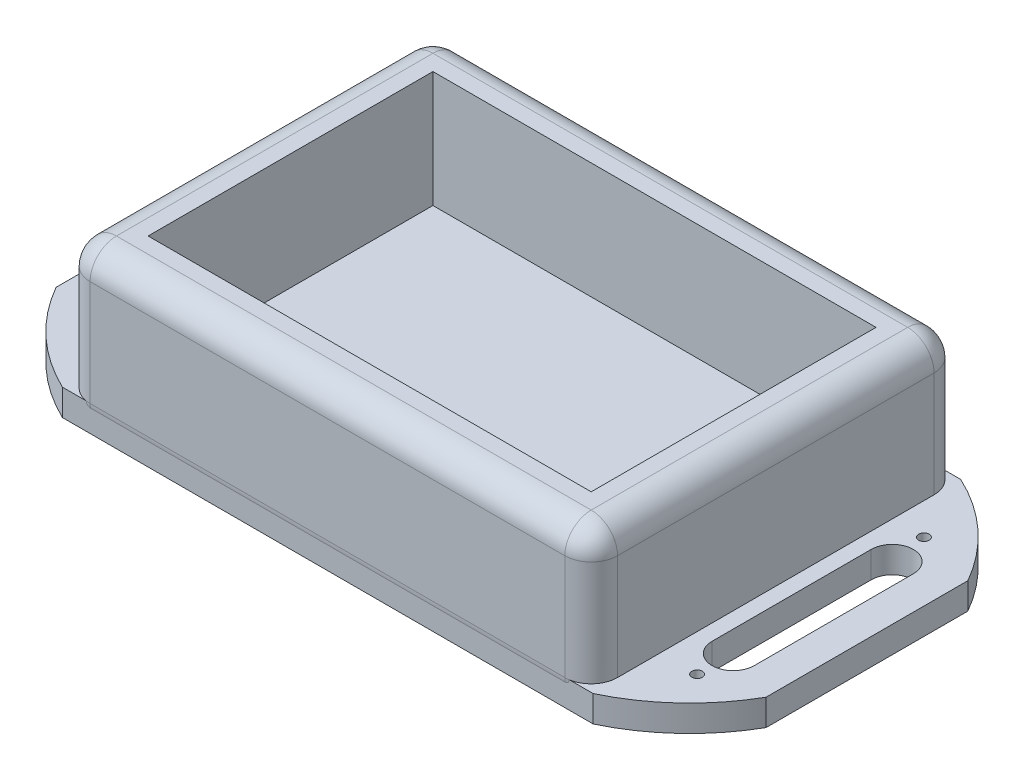
SolidWorks part; units mm, degrees
ref_plane "Front Plane" through (0, 0, 0) normal (0, 0, 1) x (1, 0, 0)
ref_plane "Top Plane" through (0, 0, 0) normal (0, 1, 0) x (1, 0, 0)
ref_plane "Right Plane" through (0, 0, 0) normal (1, 0, 0) x (0, 0, -1)
other "Center of Mass"
sketch "Sketch1" plane through (0, 0, 0) normal (0, 1, 0) x (1, 0, 0)
  line L0 (23.3839, 15.8839) -> (-23.3839, -15.8839) construction
  line L1 (-23.3839, 16.6161) -> (21.6161, 16.6161)
  line L2 (-25.8839, 14.1161) -> (-25.8839, -15.8839)
  line L3 (-23.3839, -18.3839) -> (21.6161, -18.3839)
  line L4 (24.1161, 14.1161) -> (24.1161, -15.8839)
  arc A0 (-23.3839, 16.6161) -> (-25.8839, 14.1161) centre (-23.3839, 14.1161) ccw
  arc A1 (21.6161, 16.6161) -> (24.1161, 14.1161) centre (21.6161, 14.1161) cw
  arc A2 (21.6161, -18.3839) -> (24.1161, -15.8839) centre (21.6161, -15.8839) ccw
  arc A3 (-25.8839, -15.8839) -> (-23.3839, -18.3839) centre (-23.3839, -15.8839) ccw
  point P6 (-25.8839, 16.6161)
  point P9 (24.1161, 16.6161)
  point P14 (-25.8839, -18.3839)
  point P16 (0, 0)
  dimension "D3" = 2.5
  dimension "D4" = 2.5
  dimension "D5" = 2.5
  dimension "D6" = 2.5
  dimension "D1" = 50
  dimension "D2" = 35
extrude "Boss-Extrude2" add sketch "Sketch1" along normal blind 15
fillet "Fillet2" radius 2.5 16 edges at (-25.8839, 0, 0.8839) (-25.1517, 0, 17.6517) (-0.8839, 0, 18.3839) (23.3839, 0, 17.6517) (24.1161, 0, 0.8839) (23.3839, 0, -15.8839) (-0.8839, 0, -16.6161) (-25.1517, 0, -15.8839) (-0.8839, 15, -16.6161) (23.3839, 15, -15.8839) (24.1161, 15, 0.8839) (23.3839, 15, 17.6517) (-0.8839, 15, 18.3839) (-25.1517, 15, 17.6517) (-25.8839, 15, 0.8839) (-25.1517, 15, -15.8839)
sketch "Sketch3" plane through (0, 0, 0) normal (0, 1, 0) x (1, 0, 0)
  line L0 (21.6161, 14.1161) -> (-23.3839, 14.1161) construction
  line L1 (-0.8839, 14.1161) -> (-0.8839, -15.8839)
  line L2 (-25.8839, 16.6469) -> (24.1161, 16.6469)
  line L3 (-34.5339, 8.6743) -> (-34.5339, -10.4535)
  line L4 (-26.039, -18.3531) -> (24.2713, -18.3531)
  line L6 (29.6161, 6.6585) -> (29.6161, -8.4263)
  line L7 (25.6161, 6.6585) -> (25.6161, -8.4263)
  line L8 (32.7661, 8.6743) -> (32.7661, -10.4535)
  line L9 (-23.3839, -15.8839) -> (21.6161, -15.8839) construction
  line L10 (32.7661, 8.6743) -> (32.7661, -10.4535)
  line L14 (-31.3839, 6.6585) -> (-31.3839, -8.4263)
  line L16 (-27.3839, 6.6585) -> (-27.3839, -8.4263)
  circle A0 centre (-28.8839, 10.1585) radius 0.5
  circle A1 centre (-29.3839, -11.8415) radius 0.5
  circle A2 centre (27.6161, -11.8415) radius 0.5
  circle A3 centre (27.1161, 10.1585) radius 0.5
  arc A4 (-27.3839, 6.6585) -> (-31.3839, 6.6585) centre (-29.3839, 6.6585) ccw
  arc A5 (-27.3839, -8.4263) -> (-31.3839, -8.4263) centre (-29.3839, -8.4263) cw
  arc A6 (25.6161, -8.4263) -> (29.6161, -8.4263) centre (27.6161, -8.4263) ccw
  arc A7 (25.6161, 6.6585) -> (29.6161, 6.6585) centre (27.6161, 6.6585) cw
  arc A8 (32.7661, -10.4535) -> (24.2713, -18.3531) centre (15.952, -0.8896) cw
  arc A9 (-34.5339, -10.4535) -> (-26.039, -18.3531) centre (-17.7198, -0.8896) ccw
  arc A10 (-25.8839, 16.6469) -> (-34.5339, 8.6743) centre (-17.7198, -0.8896) ccw
  arc A11 (24.1161, 16.6469) -> (32.7661, 8.6743) centre (15.952, -0.8896) cw
  dimension "D5" = 35
  dimension "D1" = 67.3
  dimension "D2" = 22
  dimension "D3" = 56
  dimension "D4" = 50
extrude "Boss-Extrude4" add sketch "Sketch3" along normal blind 2.5
other "Center of Mass Reference Point2"
sketch "Sketch4" plane through (0, 15, 0) normal (0, 1, 0) x (1, 0, 0)
  line L9 (-21.8841, 12.6165) -> (20.1187, 12.6165)
  line L10 (-21.8841, 12.6165) -> (-21.8841, -14.3846)
  line L11 (-21.8841, -14.3846) -> (20.1187, -14.3846)
  line L12 (20.1187, 12.6165) -> (20.1187, -14.3846)
  line L13 (-21.8841, 12.6165) -> (20.1187, -14.3846) construction
  line L14 (-21.8841, -14.3846) -> (20.1187, 12.6165) construction
  point P0 (-0.8827, -0.8841)
extrude "Cut-Extrude2" cut sketch "Sketch4" against normal blind 11 contours L10 L9 L12 L11
